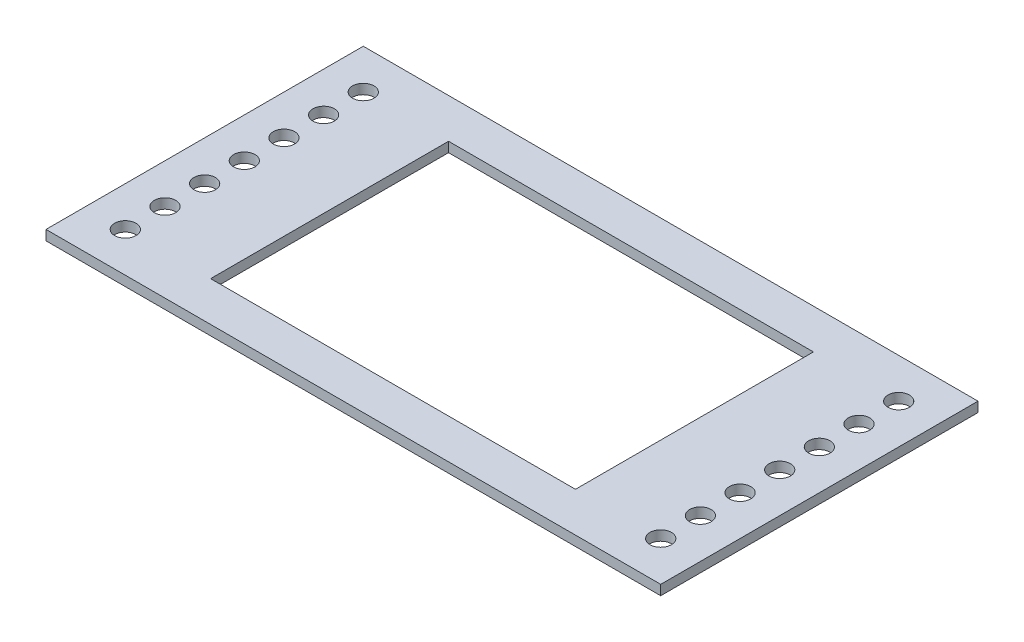
SolidWorks part; units mm, degrees
ref_plane "Front Plane" through (0, 0, 0) normal (0, 0, 1) x (1, 0, 0)
ref_plane "Top Plane" through (0, 0, 0) normal (0, 1, 0) x (1, 0, 0)
ref_plane "Right Plane" through (0, 0, 0) normal (1, 0, 0) x (0, 0, -1)
sketch "Sketch1" plane through (0, 0, 0) normal (0, 1, 0) x (1, 0, 0)
  line L1 (98.425, 50.8) -> (-98.425, 50.8)
  line L2 (98.425, 50.8) -> (98.425, -50.8)
  line L3 (98.425, -50.8) -> (-98.425, -50.8)
  line L4 (-98.425, 50.8) -> (-98.425, -50.8)
  line L5 (98.425, 50.8) -> (-98.425, -50.8) construction
  line L6 (98.425, -50.8) -> (-98.425, 50.8) construction
  line L7 (58.42, 38.1) -> (-58.42, 38.1)
  line L8 (58.42, 38.1) -> (58.42, -38.1)
  line L9 (58.42, -38.1) -> (-58.42, -38.1)
  line L10 (-58.42, 38.1) -> (-58.42, -38.1)
  line L11 (58.42, 38.1) -> (-58.42, -38.1) construction
  line L12 (58.42, -38.1) -> (-58.42, 38.1) construction
  circle A0 centre (-85.725, 38.1) radius 3.429
  circle A1 centre (85.725, 38.1) radius 3.429
  circle A2 centre (85.725, 25.4) radius 3.429
  circle A3 centre (85.725, 12.7) radius 3.429
  circle A4 centre (85.725, 0) radius 3.429
  circle A5 centre (85.725, -12.7) radius 3.429
  circle A6 centre (85.725, -25.4) radius 3.429
  circle A7 centre (85.725, -38.1) radius 3.429
  circle A8 centre (-85.725, 25.4) radius 3.429
  circle A9 centre (-85.725, 12.7) radius 3.429
  circle A10 centre (-85.725, 0) radius 3.429
  circle A11 centre (-85.725, -12.7) radius 3.429
  circle A12 centre (-85.725, -25.4) radius 3.429
  circle A13 centre (-85.725, -38.1) radius 3.429
  point P0 (0, 0)
  point P6 (0, 0)
  dimension "D5" = 6.858
  dimension "D1" = 76.2
  dimension "D2" = 101.6
  dimension "D3" = 116.84
  dimension "D4" = 196.85
  dimension "D6" = 12.7
  dimension "D7" = 12.7
  dimension "D10" = 171.45
  dimension "D8" = 2
  dimension "D9" = 7
extrude "Boss-Extrude1" add sketch "Sketch1" along normal blind 3.175
